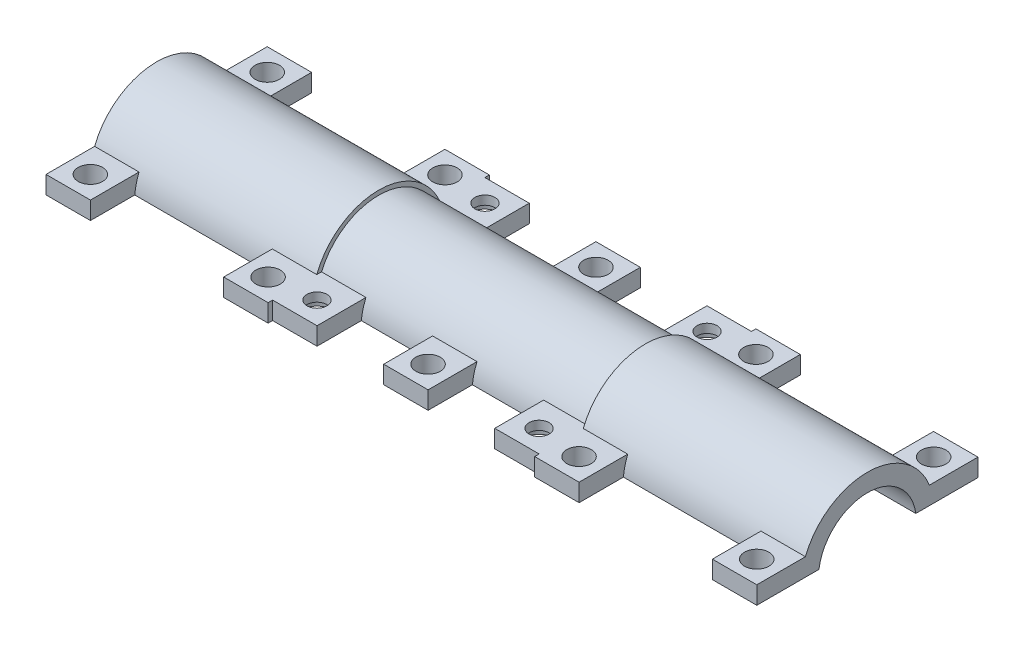
SolidWorks part; units mm, degrees
ref_plane "Front Plane" through (0, 0, 0) normal (0, 0, 1) x (1, 0, 0)
ref_plane "Top Plane" through (0, 0, 0) normal (0, 1, 0) x (1, 0, 0)
ref_plane "Right Plane" through (0, 0, 0) normal (1, 0, 0) x (0, 0, -1)
sketch "Sketch1" plane through (0, 0, 0) normal (1, 0, 0) x (0, 0, -1)
  line L0 (-49.4052, 0) -> (68.181, 0) construction
  line L1 (-13.9194, 1.5) -> (-9.8869, 1.5)
  line L2 (9.8869, 1.5) -> (13.9194, 1.5)
  arc A2 (9.8869, 1.5) -> (-9.8869, 1.5) centre (0, 0) ccw
  arc A3 (-13.9194, 1.5) -> (13.9194, 1.5) centre (0, 0) cw
  dimension "D1" = 1.5
  dimension "D2" = 10
  dimension "D3" = 14
extrude "Boss-Extrude2" add sketch "Sketch1" along normal mid plane 60
sketch "Sketch2" plane through (0, 1.5, 0) normal (0, -1, 0) x (1, 0, 0)
  line L0 (-30, -9.8869) -> (-30, -23.8869)
  line L1 (-30, -23.8869) -> (-20, -23.8869)
  line L2 (-20, -23.8869) -> (-20, -9.8869)
  line L3 (30, -9.8869) -> (-30, -9.8869) construction
  line L4 (-20, -9.8869) -> (-30, -9.8869)
  line L5 (-30, -13.9194) -> (-20, -23.8869) construction
  line L6 (-30, -23.8869) -> (-20, -13.9194) construction
  line L7 (30, -13.9194) -> (-30, -13.9194) construction
  line L8 (0, 27.2864) -> (0, -38.5559) construction
  line L9 (-39.4988, 0) -> (58.103, 0) construction
  line L10 (20, -23.8869) -> (20, -9.8869)
  line L11 (30, -23.8869) -> (20, -23.8869)
  line L12 (30, -9.8869) -> (30, -23.8869)
  line L13 (20, -9.8869) -> (30, -9.8869)
  line L14 (-20, 23.8869) -> (-20, 9.8869)
  line L15 (-30, 23.8869) -> (-20, 23.8869)
  line L16 (-30, 9.8869) -> (-30, 23.8869)
  line L17 (-20, 9.8869) -> (-30, 9.8869)
  line L18 (30, 23.8869) -> (20, 23.8869)
  line L19 (30, 9.8869) -> (30, 23.8869)
  line L20 (20, 9.8869) -> (30, 9.8869)
  line L21 (20, 23.8869) -> (20, 9.8869)
  line L22 (30, 9.8869) -> (-30, 9.8869) construction
  line L23 (-5, 9.8869) -> (5, 9.8869)
  line L24 (-5, 9.8869) -> (-5, 23.8869)
  line L25 (-5, 23.8869) -> (5, 23.8869)
  line L26 (5, 9.8869) -> (5, 23.8869)
  line L27 (-5, -23.8869) -> (5, -23.8869)
  line L28 (5, -9.8869) -> (5, -23.8869)
  line L29 (-5, -9.8869) -> (5, -9.8869)
  line L30 (-5, -9.8869) -> (-5, -23.8869)
  circle A0 centre (-25, -18.9031) radius 2.25
  circle A3 centre (25, 18.9031) radius 2.25
  circle A4 centre (25, -18.9031) radius 2.25
  circle A5 centre (-25, 18.9031) radius 2.25
  circle A6 centre (0, 18.9031) radius 2.75
  circle A7 centre (0, -18.9031) radius 2.75
  point P43 (0, 15.9033)
  point P52 (0, 0)
  dimension "D3" = 5.5
  dimension "D4" = 4.5
  dimension "D1" = 10
  dimension "D2" = 14
extrude "Boss-Extrude3" add sketch "Sketch2" against normal blind 4
sketch "Sketch6" plane through (0, 1.5, 0) normal (0, -1, 0) x (1, 0, 0)
  circle A0 centre (-25, 18.9031) radius 4
  circle A1 centre (25, -18.9031) radius 4
  circle A2 centre (-25, -18.9031) radius 4
  circle A3 centre (25, 18.9031) radius 4
  dimension "D1" = 8
extrude "Cut-Extrude1" cut sketch "Sketch6" against normal blind 2
sketch "Sketch7" plane through (-30, 0, 0) normal (-1, 0, 0) x (0, 0, 1)
  line L0 (-25.7548, 0) -> (29.9478, 0) construction
  line L1 (-9.8869, 1.5) -> (-23.8869, 1.5) construction
  line L2 (23.8869, 1.5) -> (9.8869, 1.5) construction
  line L3 (-14.9248, 1.5) -> (-10.8972, 1.5)
  line L4 (10.8972, 1.5) -> (14.9248, 1.5)
  arc A0 (-10.8972, 1.5) -> (10.8972, 1.5) centre (0, 0) cw
  arc A1 (14.9248, 1.5) -> (-14.9248, 1.5) centre (0, 0) ccw
  dimension "D1" = 11
  dimension "D2" = 15
extrude "Boss-Extrude4" add sketch "Sketch7" along normal blind 50
sketch "Sketch8" plane through (0, 1.5, 0) normal (0, -1, 0) x (1, 0, 0)
  line L0 (-80, 24.8972) -> (-70, 14.9248) construction
  line L5 (-80, 10.8972) -> (-70, 10.8972)
  line L6 (-80, 10.8972) -> (-80, 24.8972)
  line L7 (-80, 24.8972) -> (-70, 24.8972)
  line L8 (-70, 10.8972) -> (-70, 24.8972)
  line L9 (-80, 14.9248) -> (-30, 14.9248) construction
  line L10 (-80, 14.9248) -> (-70, 24.8972) construction
  line L11 (-55, 14.9248) -> (-55, -27.4846) construction
  line L12 (-95.9106, 0) -> (39.2544, 0) construction
  line L13 (-30, 24.8972) -> (-40, 24.8972)
  line L14 (-40, 10.8972) -> (-40, 24.8972)
  line L15 (-30, 10.8972) -> (-40, 10.8972)
  line L16 (-30, 10.8972) -> (-30, 24.8972)
  line L17 (-80, -24.8972) -> (-70, -24.8972)
  line L18 (-70, -10.8972) -> (-70, -24.8972)
  line L19 (-80, -10.8972) -> (-70, -10.8972)
  line L20 (-80, -10.8972) -> (-80, -24.8972)
  line L21 (-30, -10.8972) -> (-30, -24.8972)
  line L22 (-30, -10.8972) -> (-40, -10.8972)
  line L23 (-40, -10.8972) -> (-40, -24.8972)
  line L24 (-30, -24.8972) -> (-40, -24.8972)
  circle A0 centre (-75, 19.911) radius 2.75
  circle A1 centre (-35, 19.911) radius 2.75
  circle A2 centre (-75, -19.911) radius 2.75
  circle A3 centre (-35, -19.911) radius 2.75
  dimension "D3" = 5.5
  dimension "D1" = 14
  dimension "D2" = 10
extrude "Boss-Extrude5" add sketch "Sketch8" against normal blind 4
mirror "Mirror1" about plane through (0, 0, 0) normal (1, 0, 0) of "Boss-Extrude4", "Boss-Extrude5"
